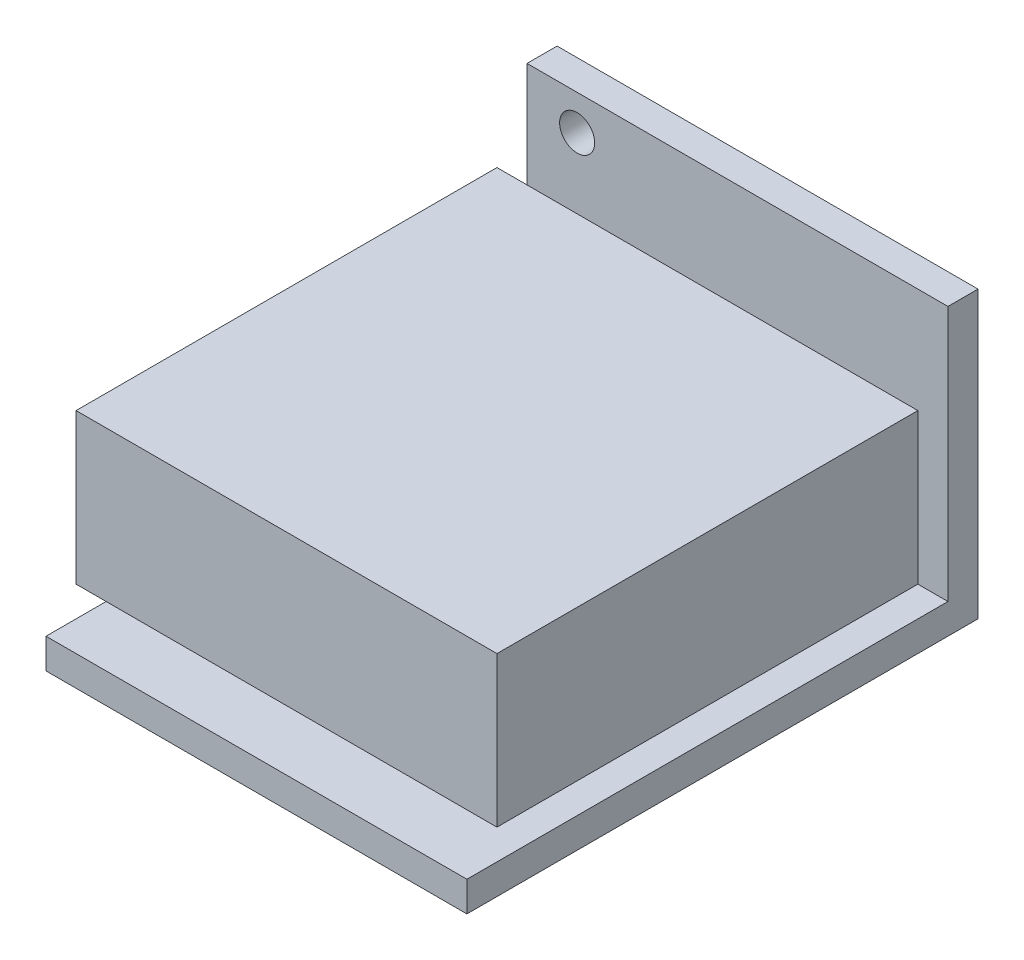
SolidWorks part; units mm, degrees
ref_plane "Alzado" through (0, 0, 0) normal (0, 0, 1) x (1, 0, 0)
ref_plane "Planta" through (0, 0, 0) normal (0, 1, 0) x (1, 0, 0)
ref_plane "Vista lateral" through (0, 0, 0) normal (1, 0, 0) x (0, 0, -1)
sketch "Croquis1" plane through (0, 0, 0) normal (0, 1, 0) x (1, 0, 0)
  line L1 (21, -21) -> (-21, -21)
  line L2 (21, -21) -> (21, 21)
  line L3 (21, 21) -> (-21, 21)
  line L4 (-21, -21) -> (-21, 21)
  line L5 (21, -21) -> (-21, 21) construction
  line L6 (21, 21) -> (-21, -21) construction
  point P0 (0, 0)
  dimension "D1" = 42
  dimension "D2" = 42
extrude "Saliente-Extruir1" add sketch "Croquis1" along normal blind 15
sketch "Croquis2" plane through (21, 0, 0) normal (1, 0, 0) x (0, 0, -1)
  line L1 (-24, -3) -> (-24, -6)
  line L2 (-24, -6) -> (27, -6)
  line L6 (27, 22.5) -> (24, 22.5)
  line L8 (27, 22.5) -> (27, -6)
  line L9 (-24, -3) -> (24, -3)
  line L10 (24, -3) -> (24, 22.5)
  line L11 (-21, 0) -> (21, 0) construction
  line L12 (-21, 15) -> (-21, 0) construction
  line L13 (21, 15) -> (21, 0) construction
  dimension "D1" = 3
  dimension "D2" = 3
  dimension "D3" = 3
  dimension "D4" = 3
  dimension "D5" = 28.5
  dimension "D6" = 3
extrude "Saliente-Extruir2" add sketch "Croquis2" against normal blind 42 separate body
sketch "Croquis3" plane through (0, 0, -24) normal (0, 0, 1) x (1, 0, 0)
  line L0 (-21, 22.5) -> (-21, -3) construction
  line L1 (-21, 15) -> (21, 15) construction
  circle A0 centre (-16, 19) radius 1.75
  circle A1 centre (-16, 19) radius 3.25 construction
  dimension "D1" = 3.5
  dimension "D4" = 6.5
  dimension "D2" = 5
  dimension "D3" = 4
extrude "Cortar-Extruir1" cut sketch "Croquis3" against normal through all
